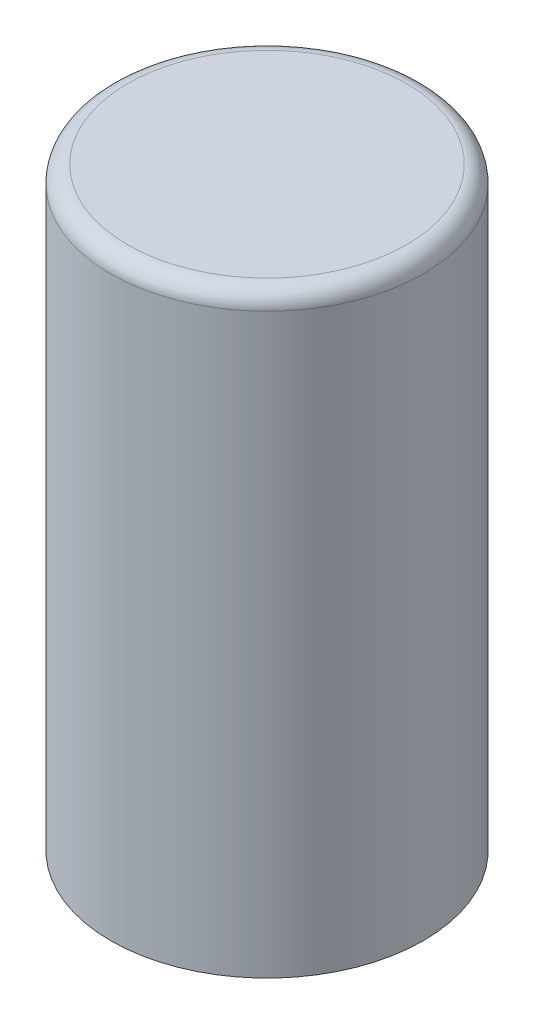
SolidWorks part; units mm, degrees
material "Brass"
ref_plane "Front" through (0, 0, 0) normal (0, 0, 1) x (1, 0, 0)
ref_plane "Top" through (0, 0, 0) normal (0, 1, 0) x (1, 0, 0)
ref_plane "Right" through (0, 0, 0) normal (1, 0, 0) x (0, 0, -1)
sketch "Sketch1" plane through (0, 0, 0) normal (0, 0, 1) x (1, 0, 0)
  line L0 (0, 0) -> (0, 5.1714) construction
  line L1 (0, 5.1714) -> (1.1811, 5.1714)
  line L2 (1.1811, 5.1714) -> (1.1811, 0.6819)
  line L3 (1.1811, 0.6819) -> (0, 0)
  line L4 (0, 0) -> (0, 5.1714)
  dimension "D1" = 2.3622
  dimension "D2" = 5.1714
  dimension "D3" = 60
revolve "Revolve1" add sketch "Sketch1" angle 360 about L0
fillet "Fillet1" radius 0.127 1 edges at (0, 5.1714, -1.1811)
equation "\"0\"= .1100"
equation "\"1\"= .1255"
equation "\"2\"= .1411"
equation "\"3\"= .1567"
equation "\"4\"= .1724"
equation "\"5\"= .1880"
equation "\"6\"= .2036"
equation "\"7\"= .2192"
equation "\"D2@Sketch1\"  = \"6\""
